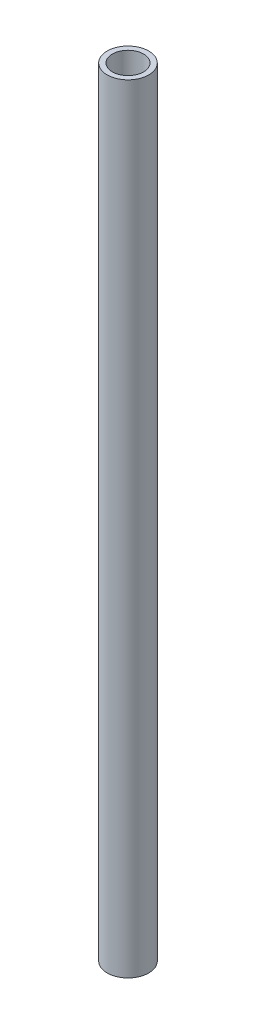
SolidWorks part; units mm, degrees
ref_plane "Front Plane" through (0, 0, 0) normal (0, 0, 1) x (1, 0, 0)
ref_plane "Top Plane" through (0, 0, 0) normal (0, 1, 0) x (1, 0, 0)
ref_plane "Right Plane" through (0, 0, 0) normal (1, 0, 0) x (0, 0, -1)
sketch "Sketch1" plane through (0, 0, 0) normal (0, 0, 1) x (1, 0, 0)
  line L0 (0, 0) -> (0, 150)
  point P6 (0, 150)
  dimension "D1" = 150
sketch "Sketch2" plane through (0, 0, 0) normal (0, 1, 0) x (1, 0, 0)
  circle A0 centre (0, 0) radius 4
  circle A1 centre (0, 0) radius 3
  dimension "D1" = 6
  dimension "D2" = 8
sweep "Sweep1" add profiles "Sketch2" path "Sketch1"
